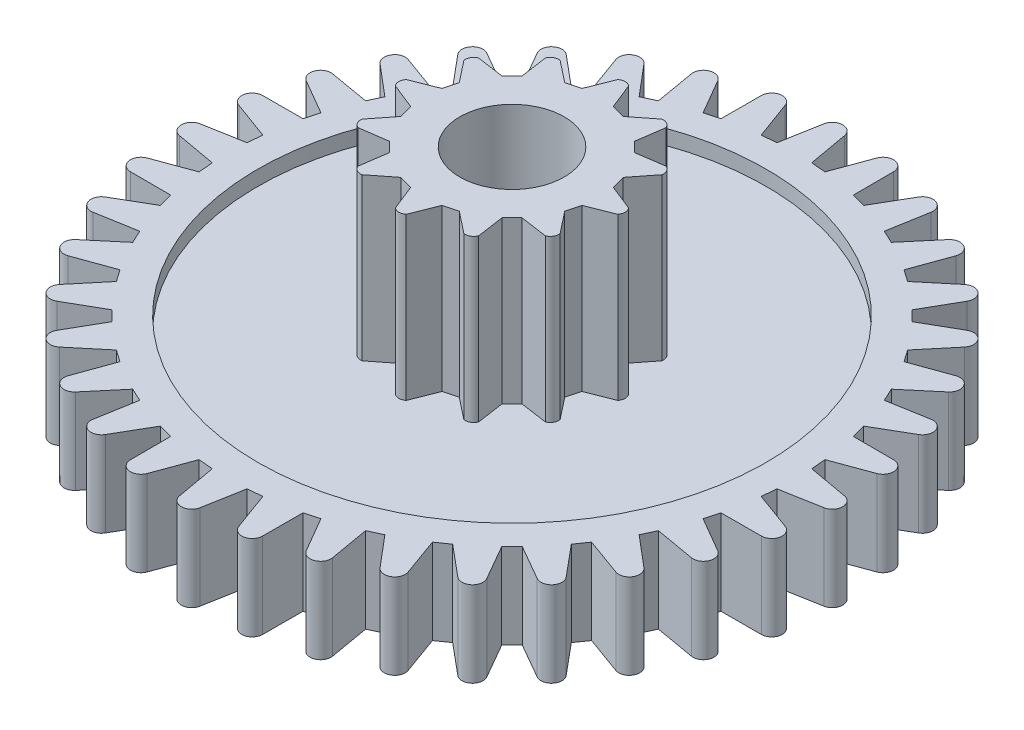
SolidWorks part; units mm, degrees
material "ABS"
ref_plane "Front Plane" through (0, 0, 0) normal (0, 0, 1) x (1, 0, 0)
ref_plane "Top Plane" through (0, 0, 0) normal (0, 1, 0) x (1, 0, 0)
ref_plane "Right Plane" through (0, 0, 0) normal (1, 0, 0) x (0, 0, -1)
sketch "Sketch1" plane through (0, 0, 0) normal (0, 0, 1) x (1, 0, 0)
  line L0 (3.25, 0.795) -> (7.3, 0.795)
  line L1 (7.3, 0.795) -> (7.3, 1.225)
  line L2 (7.3, 1.225) -> (9.5, 1.225)
  line L3 (9.5, 1.225) -> (9.5, -1.225)
  line L4 (1.5, -1.225) -> (2.5, -1.225)
  line L5 (0, -1.225) -> (0, 0) construction
  line L6 (3.25, 0.795) -> (3.25, 5.425)
  line L7 (3.25, 5.425) -> (1.5, 5.425)
  line L8 (0, 5.425) -> (0, 0) construction
  line L9 (2.5, -1.225) -> (2.5, -0.795)
  line L10 (2.5, -0.795) -> (7.3, -0.795)
  line L11 (7.3, -0.795) -> (7.3, -1.225)
  line L12 (7.3, -1.225) -> (9.5, -1.225)
  line L13 (9.5, 0) -> (0, 0) construction
  line L14 (1.5, -1.225) -> (1.5, 5.425)
  dimension "D1" = 19
  dimension "D2" = 2.2
  dimension "D3" = 6.5
  dimension "D4" = 6.65
  dimension "D5" = 2.45
  dimension "D6" = 4.63
  dimension "D7" = 5
  dimension "D8" = 3
revolve "Revolve1" add sketch "Sketch1" angle 360 about L8
sketch "Sketch2" plane through (0, 1.225, 0) normal (0, 1, 0) x (1, 0, 0)
  line L0 (0, 0) -> (0, 8.125) construction
  line L1 (0, 8.125) -> (0, 9.2) construction
  line L2 (-0.2953, 9.2529) -> (-0.5, 8.1096)
  line L3 (0, 9.2) -> (0, 9.5) construction
  line L4 (0.2953, 9.2529) -> (0.5, 8.1096)
  line L5 (1.8976, 9.061) -> (1.9006, 7.8996)
  line L6 (1.3159, 9.1636) -> (0.9158, 8.0732)
  line L7 (3.4422, 8.5939) -> (3.2435, 7.4495)
  line L8 (2.8872, 8.7959) -> (2.3038, 7.7915)
  line L9 (4.8822, 7.8656) -> (4.4878, 6.7731)
  line L10 (4.3707, 8.1609) -> (3.6218, 7.2731)
  line L11 (6.1738, 6.8983) -> (5.5958, 5.8909)
  line L12 (5.7214, 7.2779) -> (4.8297, 6.5337)
  line L13 (7.2779, 5.7214) -> (6.5337, 4.8297)
  line L14 (6.8983, 6.1738) -> (5.8909, 5.5958)
  line L15 (8.1609, 4.3707) -> (7.2731, 3.6218)
  line L16 (7.8656, 4.8822) -> (6.7731, 4.4878)
  line L17 (8.7959, 2.8872) -> (7.7915, 2.3038)
  line L18 (8.5939, 3.4422) -> (7.4495, 3.2435)
  line L19 (9.1636, 1.3159) -> (8.0732, 0.9158)
  line L20 (9.061, 1.8976) -> (7.8996, 1.9006)
  line L21 (9.2529, -0.2953) -> (8.1096, -0.5)
  line L22 (9.2529, 0.2953) -> (8.1096, 0.5)
  line L23 (9.061, -1.8976) -> (7.8996, -1.9006)
  line L24 (9.1636, -1.3159) -> (8.0732, -0.9158)
  line L25 (8.5939, -3.4422) -> (7.4495, -3.2435)
  line L26 (8.7959, -2.8872) -> (7.7915, -2.3038)
  line L27 (7.8656, -4.8822) -> (6.7731, -4.4878)
  line L28 (8.1609, -4.3707) -> (7.2731, -3.6218)
  line L29 (6.8983, -6.1738) -> (5.8909, -5.5958)
  line L30 (7.2779, -5.7214) -> (6.5337, -4.8297)
  line L31 (5.7214, -7.2779) -> (4.8297, -6.5337)
  line L32 (6.1738, -6.8983) -> (5.5958, -5.8909)
  line L33 (4.3707, -8.1609) -> (3.6218, -7.2731)
  line L34 (4.8822, -7.8656) -> (4.4878, -6.7731)
  line L35 (2.8872, -8.7959) -> (2.3038, -7.7915)
  line L36 (3.4422, -8.5939) -> (3.2435, -7.4495)
  line L37 (1.3159, -9.1636) -> (0.9158, -8.0732)
  line L38 (1.8976, -9.061) -> (1.9006, -7.8996)
  line L39 (-0.2953, -9.2529) -> (-0.5, -8.1096)
  line L40 (0.2953, -9.2529) -> (0.5, -8.1096)
  line L41 (-1.8976, -9.061) -> (-1.9006, -7.8996)
  line L42 (-1.3159, -9.1636) -> (-0.9158, -8.0732)
  line L43 (-3.4422, -8.5939) -> (-3.2435, -7.4495)
  line L44 (-2.8872, -8.7959) -> (-2.3038, -7.7915)
  line L45 (-4.8822, -7.8656) -> (-4.4878, -6.7731)
  line L46 (-4.3707, -8.1609) -> (-3.6218, -7.2731)
  line L47 (-6.1738, -6.8983) -> (-5.5958, -5.8909)
  line L48 (-5.7214, -7.2779) -> (-4.8297, -6.5337)
  line L49 (-7.2779, -5.7214) -> (-6.5337, -4.8297)
  line L50 (-6.8983, -6.1738) -> (-5.8909, -5.5958)
  line L51 (-8.1609, -4.3707) -> (-7.2731, -3.6218)
  line L52 (-7.8656, -4.8822) -> (-6.7731, -4.4878)
  line L53 (-8.7959, -2.8872) -> (-7.7915, -2.3038)
  line L54 (-8.5939, -3.4422) -> (-7.4495, -3.2435)
  line L55 (-9.1636, -1.3159) -> (-8.0732, -0.9158)
  line L56 (-9.061, -1.8976) -> (-7.8996, -1.9006)
  line L57 (-9.2529, 0.2953) -> (-8.1096, 0.5)
  line L58 (-9.2529, -0.2953) -> (-8.1096, -0.5)
  line L59 (-9.061, 1.8976) -> (-7.8996, 1.9006)
  line L60 (-9.1636, 1.3159) -> (-8.0732, 0.9158)
  line L61 (-8.5939, 3.4422) -> (-7.4495, 3.2435)
  line L62 (-8.7959, 2.8872) -> (-7.7915, 2.3038)
  line L63 (-7.8656, 4.8822) -> (-6.7731, 4.4878)
  line L64 (-8.1609, 4.3707) -> (-7.2731, 3.6218)
  line L65 (-6.8983, 6.1738) -> (-5.8909, 5.5958)
  line L66 (-7.2779, 5.7214) -> (-6.5337, 4.8297)
  line L67 (-5.7214, 7.2779) -> (-4.8297, 6.5337)
  line L68 (-6.1738, 6.8983) -> (-5.5958, 5.8909)
  line L69 (-4.3707, 8.1609) -> (-3.6218, 7.2731)
  line L70 (-4.8822, 7.8656) -> (-4.4878, 6.7731)
  line L71 (-2.8872, 8.7959) -> (-2.3038, 7.7915)
  line L72 (-3.4422, 8.5939) -> (-3.2435, 7.4495)
  line L73 (-1.3159, 9.1636) -> (-0.9158, 8.0732)
  line L74 (-1.8976, 9.061) -> (-1.9006, 7.8996)
  line L75 (0.5, 8.1096) -> (0.9158, 8.0732)
  line L76 (1.9006, 7.8996) -> (2.3038, 7.7915)
  line L77 (3.2435, 7.4495) -> (3.6218, 7.2731)
  line L78 (4.4878, 6.7731) -> (4.8297, 6.5337)
  line L79 (5.5958, 5.8909) -> (5.8909, 5.5958)
  line L80 (6.5337, 4.8297) -> (6.7731, 4.4878)
  line L81 (7.2731, 3.6218) -> (7.4495, 3.2435)
  line L82 (7.7915, 2.3038) -> (7.8996, 1.9006)
  line L83 (8.0732, 0.9158) -> (8.1096, 0.5)
  line L84 (8.1096, -0.5) -> (8.0732, -0.9158)
  line L85 (7.8996, -1.9006) -> (7.7915, -2.3038)
  line L86 (7.4495, -3.2435) -> (7.2731, -3.6218)
  line L87 (6.7731, -4.4878) -> (6.5337, -4.8297)
  line L88 (5.8909, -5.5958) -> (5.5958, -5.8909)
  line L89 (4.8297, -6.5337) -> (4.4878, -6.7731)
  line L90 (3.6218, -7.2731) -> (3.2435, -7.4495)
  line L91 (2.3038, -7.7915) -> (1.9006, -7.8996)
  line L92 (0.9158, -8.0732) -> (0.5, -8.1096)
  line L93 (-0.5, -8.1096) -> (-0.9158, -8.0732)
  line L94 (-1.9006, -7.8996) -> (-2.3038, -7.7915)
  line L95 (-3.2435, -7.4495) -> (-3.6218, -7.2731)
  line L96 (-4.4878, -6.7731) -> (-4.8297, -6.5337)
  line L97 (-5.5958, -5.8909) -> (-5.8909, -5.5958)
  line L98 (-6.5337, -4.8297) -> (-6.7731, -4.4878)
  line L99 (-7.2731, -3.6218) -> (-7.4495, -3.2435)
  line L100 (-7.7915, -2.3038) -> (-7.8996, -1.9006)
  line L101 (-8.0732, -0.9158) -> (-8.1096, -0.5)
  line L102 (-8.1096, 0.5) -> (-8.0732, 0.9158)
  line L103 (-7.8996, 1.9006) -> (-7.7915, 2.3038)
  line L104 (-7.4495, 3.2435) -> (-7.2731, 3.6218)
  line L105 (-6.7731, 4.4878) -> (-6.5337, 4.8297)
  line L106 (-5.8909, 5.5958) -> (-5.5958, 5.8909)
  line L107 (-4.8297, 6.5337) -> (-4.4878, 6.7731)
  line L108 (-3.6218, 7.2731) -> (-3.2435, 7.4495)
  line L109 (-2.3038, 7.7915) -> (-1.9006, 7.8996)
  line L110 (-0.9158, 8.0732) -> (-0.5, 8.1096)
  line L111 (0, 0) -> (-9.5, 9.5) construction
  circle A0 centre (0, 0) radius 8.125 construction
  arc A1 (0.2953, 9.2529) -> (-0.2953, 9.2529) centre (0, 9.2) ccw
  circle A2 centre (0, 0) radius 9.5 construction
  arc A3 (1.8976, 9.061) -> (1.3159, 9.1636) centre (1.5976, 9.0602) ccw
  arc A4 (3.4422, 8.5939) -> (2.8872, 8.7959) centre (3.1466, 8.6452) ccw
  arc A5 (4.8822, 7.8656) -> (4.3707, 8.1609) centre (4.6, 7.9674) ccw
  arc A6 (6.1738, 6.8983) -> (5.7214, 7.2779) centre (5.9136, 7.0476) ccw
  arc A7 (7.2779, 5.7214) -> (6.8983, 6.1738) centre (7.0476, 5.9136) ccw
  arc A8 (8.1609, 4.3707) -> (7.8656, 4.8822) centre (7.9674, 4.6) ccw
  arc A9 (8.7959, 2.8872) -> (8.5939, 3.4422) centre (8.6452, 3.1466) ccw
  arc A10 (9.1636, 1.3159) -> (9.061, 1.8976) centre (9.0602, 1.5976) ccw
  arc A11 (9.2529, -0.2953) -> (9.2529, 0.2953) centre (9.2, 0) ccw
  arc A12 (9.061, -1.8976) -> (9.1636, -1.3159) centre (9.0602, -1.5976) ccw
  arc A13 (8.5939, -3.4422) -> (8.7959, -2.8872) centre (8.6452, -3.1466) ccw
  arc A14 (7.8656, -4.8822) -> (8.1609, -4.3707) centre (7.9674, -4.6) ccw
  arc A15 (6.8983, -6.1738) -> (7.2779, -5.7214) centre (7.0476, -5.9136) ccw
  arc A16 (5.7214, -7.2779) -> (6.1738, -6.8983) centre (5.9136, -7.0476) ccw
  arc A17 (4.3707, -8.1609) -> (4.8822, -7.8656) centre (4.6, -7.9674) ccw
  arc A18 (2.8872, -8.7959) -> (3.4422, -8.5939) centre (3.1466, -8.6452) ccw
  arc A19 (1.3159, -9.1636) -> (1.8976, -9.061) centre (1.5976, -9.0602) ccw
  arc A20 (-0.2953, -9.2529) -> (0.2953, -9.2529) centre (0, -9.2) ccw
  arc A21 (-1.8976, -9.061) -> (-1.3159, -9.1636) centre (-1.5976, -9.0602) ccw
  arc A22 (-3.4422, -8.5939) -> (-2.8872, -8.7959) centre (-3.1466, -8.6452) ccw
  arc A23 (-4.8822, -7.8656) -> (-4.3707, -8.1609) centre (-4.6, -7.9674) ccw
  arc A24 (-6.1738, -6.8983) -> (-5.7214, -7.2779) centre (-5.9136, -7.0476) ccw
  arc A25 (-7.2779, -5.7214) -> (-6.8983, -6.1738) centre (-7.0476, -5.9136) ccw
  arc A26 (-8.1609, -4.3707) -> (-7.8656, -4.8822) centre (-7.9674, -4.6) ccw
  arc A27 (-8.7959, -2.8872) -> (-8.5939, -3.4422) centre (-8.6452, -3.1466) ccw
  arc A28 (-9.1636, -1.3159) -> (-9.061, -1.8976) centre (-9.0602, -1.5976) ccw
  arc A29 (-9.2529, 0.2953) -> (-9.2529, -0.2953) centre (-9.2, 0) ccw
  arc A30 (-9.061, 1.8976) -> (-9.1636, 1.3159) centre (-9.0602, 1.5976) ccw
  arc A31 (-8.5939, 3.4422) -> (-8.7959, 2.8872) centre (-8.6452, 3.1466) ccw
  arc A32 (-7.8656, 4.8822) -> (-8.1609, 4.3707) centre (-7.9674, 4.6) ccw
  arc A33 (-6.8983, 6.1738) -> (-7.2779, 5.7214) centre (-7.0476, 5.9136) ccw
  arc A34 (-5.7214, 7.2779) -> (-6.1738, 6.8983) centre (-5.9136, 7.0476) ccw
  arc A35 (-4.3707, 8.1609) -> (-4.8822, 7.8656) centre (-4.6, 7.9674) ccw
  arc A36 (-2.8872, 8.7959) -> (-3.4422, 8.5939) centre (-3.1466, 8.6452) ccw
  arc A37 (-1.3159, 9.1636) -> (-1.8976, 9.061) centre (-1.5976, 9.0602) ccw
  circle A38 centre (0, 0) radius 13.435
  point P14 (-9.5, 9.5)
  point P191 (0, 0)
  point P262 (0, 0)
  dimension "D1" = 16.25
  dimension "D2" = 0.3
  dimension "D3" = 1
  dimension "D4" = 36
  dimension "D6" = 45
  dimension "D5" = 36
extrude "Cut-Extrude1" cut sketch "Sketch2" against normal up to surface (2.45 mm away) up to face at (0, -1.225, 9.5)
sketch "Sketch3" plane through (0, 5.425, 0) normal (0, 1, 0) x (1, 0, 0)
  line L0 (0, 0) -> (0, 3.25) construction
  line L1 (-0.45, 2.4592) -> (-0.1557, 3.1956)
  line L2 (0.45, 2.4592) -> (0.1557, 3.1956)
  line L3 (1.6193, 1.9047) -> (1.7326, 2.6897)
  line L4 (0.8399, 2.3547) -> (1.463, 2.8453)
  line L5 (2.3547, 0.8399) -> (2.8453, 1.463)
  line L6 (1.9047, 1.6193) -> (2.6897, 1.7326)
  line L7 (2.4592, -0.45) -> (3.1956, -0.1557)
  line L8 (2.4592, 0.45) -> (3.1956, 0.1557)
  line L9 (1.9047, -1.6193) -> (2.6897, -1.7326)
  line L10 (2.3547, -0.8399) -> (2.8453, -1.463)
  line L11 (0.8399, -2.3547) -> (1.463, -2.8453)
  line L12 (1.6193, -1.9047) -> (1.7326, -2.6897)
  line L13 (-0.45, -2.4592) -> (-0.1557, -3.1956)
  line L14 (0.45, -2.4592) -> (0.1557, -3.1956)
  line L15 (-1.6193, -1.9047) -> (-1.7326, -2.6897)
  line L16 (-0.8399, -2.3547) -> (-1.463, -2.8453)
  line L17 (-2.3547, -0.8399) -> (-2.8453, -1.463)
  line L18 (-1.9047, -1.6193) -> (-2.6897, -1.7326)
  line L19 (-2.4592, 0.45) -> (-3.1956, 0.1557)
  line L20 (-2.4592, -0.45) -> (-3.1956, -0.1557)
  line L21 (-1.9047, 1.6193) -> (-2.6897, 1.7326)
  line L22 (-2.3547, 0.8399) -> (-2.8453, 1.463)
  line L23 (-0.8399, 2.3547) -> (-1.463, 2.8453)
  line L24 (-1.6193, 1.9047) -> (-1.7326, 2.6897)
  line L25 (0.45, 2.4592) -> (0.8399, 2.3547)
  line L26 (1.6193, 1.9047) -> (1.9047, 1.6193)
  line L27 (2.3547, 0.8399) -> (2.4592, 0.45)
  line L28 (2.4592, -0.45) -> (2.3547, -0.8399)
  line L29 (1.9047, -1.6193) -> (1.6193, -1.9047)
  line L30 (0.8399, -2.3547) -> (0.45, -2.4592)
  line L31 (-0.45, -2.4592) -> (-0.8399, -2.3547)
  line L32 (-1.6193, -1.9047) -> (-1.9047, -1.6193)
  line L33 (-2.3547, -0.8399) -> (-2.4592, -0.45)
  line L34 (-2.4592, 0.45) -> (-2.3547, 0.8399)
  line L35 (-1.9047, 1.6193) -> (-1.6193, 1.9047)
  line L36 (-0.8399, 2.3547) -> (-0.45, 2.4592)
  line L37 (0, 0) -> (-3.25, 3.25) construction
  arc A1 (1.7326, 2.6897) -> (1.463, 2.8453) centre (1.5, 2.5981) ccw
  circle A2 centre (0, 0) radius 2.5 construction
  arc A3 (0.1557, 3.1956) -> (-0.1557, 3.1956) centre (0, 3) ccw
  arc A4 (2.8453, 1.463) -> (2.6897, 1.7326) centre (2.5981, 1.5) ccw
  arc A5 (3.1956, -0.1557) -> (3.1956, 0.1557) centre (3, 0) ccw
  arc A6 (2.6897, -1.7326) -> (2.8453, -1.463) centre (2.5981, -1.5) ccw
  arc A7 (1.463, -2.8453) -> (1.7326, -2.6897) centre (1.5, -2.5981) ccw
  arc A8 (-0.1557, -3.1956) -> (0.1557, -3.1956) centre (0, -3) ccw
  arc A9 (-1.7326, -2.6897) -> (-1.463, -2.8453) centre (-1.5, -2.5981) ccw
  arc A10 (-2.8453, -1.463) -> (-2.6897, -1.7326) centre (-2.5981, -1.5) ccw
  arc A11 (-3.1956, 0.1557) -> (-3.1956, -0.1557) centre (-3, 0) ccw
  arc A12 (-2.6897, 1.7326) -> (-2.8453, 1.463) centre (-2.5981, 1.5) ccw
  arc A13 (-1.463, 2.8453) -> (-1.7326, 2.6897) centre (-1.5, 2.5981) ccw
  circle A14 centre (0, 0) radius 4.5962
  circle A15 centre (0, 0) radius 3.25 construction
  point P68 (0, 0)
  point P90 (0, 0)
  dimension "D1" = 0.25
  dimension "D2" = 5
  dimension "D3" = 0.9
  dimension "D4" = 12
  dimension "D6" = 45
  dimension "D5" = 12
extrude "Cut-Extrude2" cut sketch "Sketch3" against normal up to surface (4.63 mm away) up to face at (0, 0.795, 3.25)
